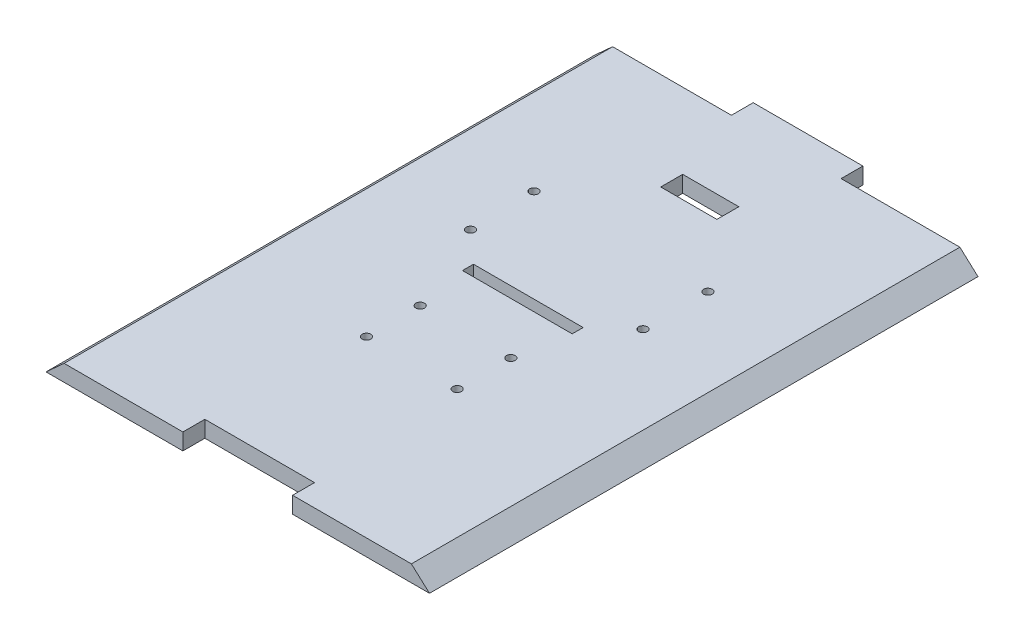
SolidWorks part; units mm, degrees
ref_plane "Front Plane" through (0, 0, 0) normal (0, 0, 1) x (1, 0, 0)
ref_plane "Top Plane" through (0, 0, 0) normal (0, 1, 0) x (1, 0, 0)
ref_plane "Right Plane" through (0, 0, 0) normal (1, 0, 0) x (0, 0, -1)
sketch "Sketch1" plane through (0, 0, 0) normal (0, 0, 1) x (1, 0, 0)
  line L0 (0, 0) -> (0, 44.45) construction
  line L1 (-40.2039, 5.9378) -> (40.2039, 5.9378)
  line L2 (-44.399, 2.1278) -> (44.399, 2.1278)
  line L3 (-40.2039, 5.9378) -> (-44.399, 2.1278)
  line L4 (40.2039, 5.9378) -> (44.399, 2.1278)
  arc A0 (44.399, 2.1278) -> (-44.399, 2.1278) centre (0, 0) ccw construction
  arc A1 (40.2039, 5.9378) -> (-40.2039, 5.9378) centre (0, 0) ccw construction
  dimension "D1" = 88.9
  dimension "D2" = 3.81
  dimension "D3" = 3.81
extrude "Boss-Extrude1" add sketch "Sketch1" along normal blind 127
sketch "Sketch3" plane through (0, 2.1278, 0) normal (0, -1, 0) x (1, 0, 0)
  line L0 (0, 127) -> (0, 0) construction
  line L1 (-44.399, 127) -> (44.399, 127) construction
  line L2 (-44.399, 0) -> (44.399, 0) construction
  line L3 (0, 63.5) -> (44.399, 63.5) construction
  line L4 (-12.7, 127) -> (12.7, 127)
  line L5 (-12.7, 127) -> (-12.7, 121.92)
  line L6 (-12.7, 121.92) -> (12.7, 121.92)
  line L7 (12.7, 127) -> (12.7, 121.92)
  line L8 (44.399, 127) -> (44.399, 0) construction
  line L9 (0, 63.5) -> (-44.399, 63.5) construction
  line L10 (-44.399, 127) -> (-44.399, 0) construction
  line L11 (12.7, -5.08) -> (12.7, 0) construction
  line L13 (-12.7, 0) -> (12.7, 0) construction
  line L14 (-12.7, -5.08) -> (-12.7, 0) construction
  line L15 (-12.7, -5.08) -> (12.7, -5.08) construction
  point P10 (12.7, 124.46)
  dimension "D1" = 25.4
  dimension "D2" = 12.7
  dimension "D3" = 5.08
extrude "Cut-Extrude1" cut sketch "Sketch3" against normal through all
sketch "Sketch4" plane through (0, 2.1278, 0) normal (0, -1, 0) x (1, 0, 0)
  line L0 (12.7, -5.0447) -> (12.7, 0.0353)
  line L1 (-12.7, 0.0353) -> (12.7, 0.0353)
  line L2 (-12.7, -5.0447) -> (-12.7, 0.0353)
  line L3 (-12.7, -5.0447) -> (12.7, -5.0447)
  line L4 (0, 121.92) -> (0, 0.0353) construction
  line L5 (-12.7, 121.92) -> (12.7, 121.92) construction
  dimension "D1" = 25.4
  dimension "D2" = 12.7
  dimension "D3" = 5.08
extrude "Boss-Extrude3" add sketch "Sketch4" against normal blind 3.81
sketch "Sketch5" plane through (0, 2.1278, 0) normal (0, -1, 0) x (-1, 0, 0)
  line L0 (0, -121.92) -> (0, 5.0447) construction
  line L1 (12.7, -121.92) -> (-12.7, -121.92) construction
  line L2 (12.7, 5.0447) -> (-12.7, 5.0447) construction
  line L3 (0, -88.6813) -> (0, -64.8053) construction
  line L4 (12.446, -88.6813) -> (-12.446, -88.6813) construction
  line L5 (12.446, -88.6813) -> (12.446, -64.8053) construction
  line L6 (12.446, -64.8053) -> (-12.446, -64.8053) construction
  line L7 (-12.446, -88.6813) -> (-12.446, -64.8053) construction
  line L8 (22.5, -55.56) -> (-22.5, -55.56) construction
  line L9 (22.5, -55.56) -> (22.5, -35.56) construction
  line L10 (22.5, -35.56) -> (-22.5, -35.56) construction
  line L11 (-22.5, -55.56) -> (-22.5, -35.56) construction
  line L12 (0, -55.56) -> (0, -35.56) construction
  line L13 (-22.5, -45.56) -> (22.5, -45.56) construction
  line L14 (12.446, -76.7433) -> (-12.446, -76.7433) construction
  line L15 (-95.9311, -70.6497) -> (-70.9311, -70.6497) construction
  line L16 (-95.9311, -70.6497) -> (-95.9311, -94.6497) construction
  line L17 (-95.9311, -94.6497) -> (-70.9311, -94.6497) construction
  line L18 (-70.9311, -70.6497) -> (-70.9311, -94.6497) construction
  line L19 (-73.5448, 8.1415) -> (-73.5448, -11.8585) construction
  line L20 (-96.4048, 8.1415) -> (-50.6848, 8.1415) construction
  line L21 (-96.4048, 8.1415) -> (-96.4048, -11.8585) construction
  line L22 (-96.4048, -11.8585) -> (-50.6848, -11.8585) construction
  line L23 (-50.6848, 8.1415) -> (-50.6848, -11.8585) construction
  line L24 (-96.4048, -1.8585) -> (-50.6848, -1.8585) construction
  line L25 (0, -17.48) -> (0, -22.56) construction
  line L26 (6.5, -17.48) -> (-6.5, -17.48)
  line L27 (6.5, -17.48) -> (6.5, -22.56)
  line L28 (6.5, -22.56) -> (-6.5, -22.56)
  line L29 (-6.5, -17.48) -> (-6.5, -22.56)
  line L30 (-12.7, 0) -> (-44.399, 0) construction
  line L31 (0, -62.2653) -> (0, -59.7253) construction
  line L32 (12.7, -62.2653) -> (-12.7, -62.2653)
  line L33 (12.7, -62.2653) -> (12.7, -59.7253)
  line L34 (12.7, -59.7253) -> (-12.7, -59.7253)
  line L35 (-12.7, -62.2653) -> (-12.7, -59.7253)
  circle A0 centre (-19.96, -38.1) radius 1
  circle A1 centre (20.313, -38.1) radius 1
  circle A2 centre (19.96, -53.1428) radius 1
  circle A3 centre (-19.96, -53.1428) radius 1
  circle A4 centre (-10.4422, -74.2033) radius 1
  circle A5 centre (-10.4422, -86.6493) radius 1
  circle A6 centre (10.5578, -74.2033) radius 1
  circle A7 centre (10.5578, -86.6493) radius 1
  circle A8 centre (-93.9311, -72.6497) radius 1
  circle A9 centre (-93.9311, -85.1497) radius 1
  circle A10 centre (-72.9311, -72.6497) radius 1
  circle A11 centre (-72.9311, -85.1497) radius 1
  circle A12 centre (-93.9048, 5.6415) radius 1
  circle A13 centre (-53.1848, 5.6415) radius 1
  circle A14 centre (-53.1848, -9.3585) radius 1
  circle A15 centre (-93.9048, -9.3585) radius 1
  point P53 (0, -20.02)
  dimension "D5" = 5.08
  dimension "D8" = 25.4
  dimension "D9" = 2.54
  dimension "D10" = 2.54
  dimension "D11" = 2.54
  dimension "D14" = 9.398
  dimension "D20" = 2
  dimension "D21" = 25
  dimension "D23" = 2
  dimension "D34" = 2
  dimension "D1" = 24.892
  dimension "D2" = 23.876
  dimension "D3" = 0
  dimension "D4" = 0
  dimension "D6" = 2.54
  dimension "D7" = 2.4172
  dimension "D12" = 45
  dimension "D13" = 20
  dimension "D15" = 9.398
  dimension "D16" = 2.032
  dimension "D17" = 2.032
  dimension "D18" = 21
  dimension "D19" = 21
  dimension "D22" = 24
  dimension "D24" = 21
  dimension "D25" = 12.5
  dimension "D26" = 9.5
  dimension "D27" = 2
  dimension "D28" = 2
  dimension "D29" = 2
  dimension "D30" = 12.446
  dimension "D31" = 2.0038
  dimension "D32" = 20
  dimension "D33" = 45.72
  dimension "D35" = 2.5
  dimension "D36" = 2.5
  dimension "D37" = 13
  dimension "D38" = 13
  dimension "D39" = 0
  dimension "D40" = 69.85
  dimension "D41" = 35.56
  dimension "D42" = 0
  dimension "D43" = 2.54
  dimension "D44" = 2.54
extrude "Cut-Extrude2" cut sketch "Sketch5" against normal through all
